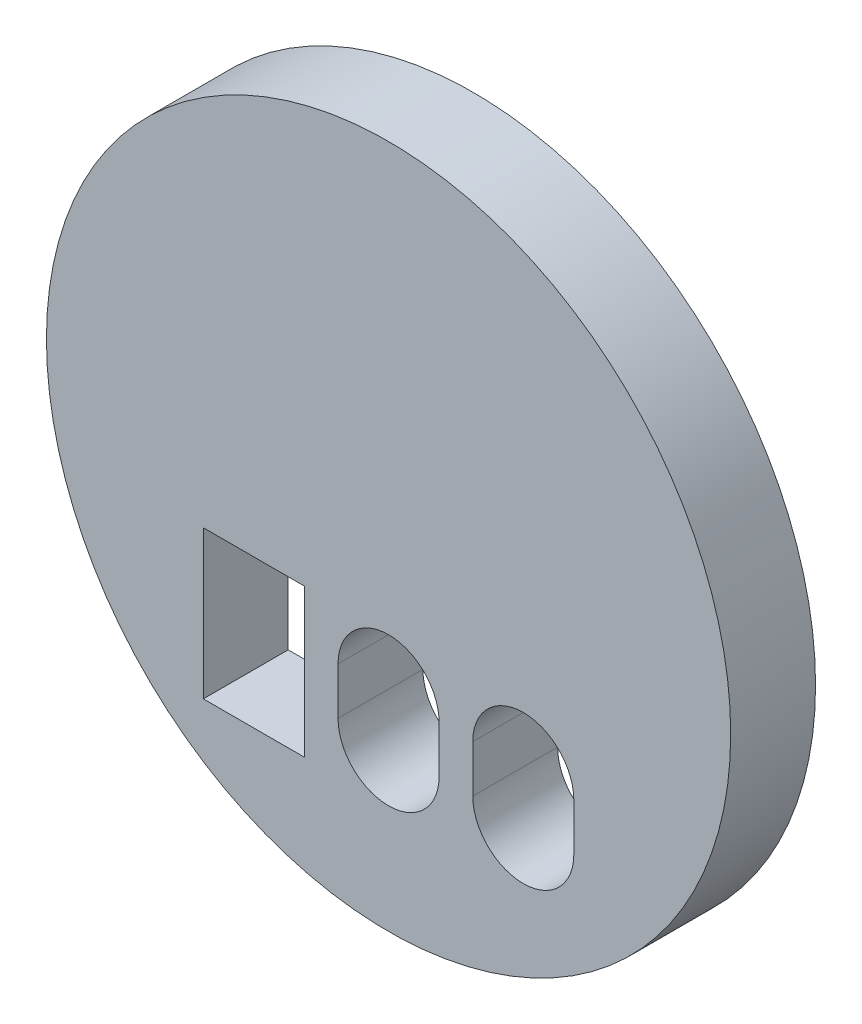
SolidWorks part; units mm, degrees
ref_plane "Plan de face" through (0, 0, 0) normal (0, 0, 1) x (1, 0, 0)
ref_plane "Plan de dessus" through (0, 0, 0) normal (0, 1, 0) x (1, 0, 0)
ref_plane "Plan de droite" through (0, 0, 0) normal (1, 0, 0) x (0, 0, -1)
sketch "Model" plane through (0, 0, 0) normal (0, 0, 1) x (1, 0, 0)
  line L0 (-3.4925, -4.397) -> (-3.4925, -1.603)
  line L1 (-3.4925, -1.603) -> (-1.5875, -1.603)
  line L2 (-1.5875, -1.603) -> (-1.5875, -4.397)
  line L3 (-1.5875, -4.397) -> (-3.4925, -4.397)
  line L4 (0.9525, -2.5555) -> (0.9525, -3.4445)
  line L5 (-0.9525, -3.4445) -> (-0.9525, -2.5555)
  line L6 (3.4925, -2.5555) -> (3.4925, -3.4445)
  line L7 (1.5875, -3.4445) -> (1.5875, -2.5555)
  line L8 (0.785, 3.92) -> (1.375, 3.92) construction
  line L9 (1.375, 3.92) -> (1.375, 3.28) construction
  line L10 (1.375, 3.28) -> (0.785, 3.28) construction
  line L11 (0.785, 3.28) -> (0.785, 3.92) construction
  line L12 (-0.175, 3.92) -> (0.415, 3.92) construction
  line L13 (0.415, 3.92) -> (0.415, 3.28) construction
  line L14 (0.415, 3.28) -> (-0.175, 3.28) construction
  line L15 (-0.175, 3.28) -> (-0.175, 3.92) construction
  line L16 (0.005, -0.612) -> (0.005, -0.305) construction
  line L17 (-0.005, -0.305) -> (-0.005, -0.612) construction
  circle A0 centre (-0.966, 2.103) radius 0.3615 construction
  circle A1 centre (1.015, -0.634) radius 0.281 construction
  circle A2 centre (-1.015, -0.634) radius 0.281 construction
  circle A3 centre (0.966, 2.103) radius 0.3615 construction
  circle A4 centre (0, 2.103) radius 0.306 construction
  arc A5 (-0.9525, -3.4445) -> (0.9525, -3.4445) centre (0, -3.4445) ccw
  arc A6 (0.9525, -2.5555) -> (-0.9525, -2.5555) centre (0, -2.5555) ccw
  arc A7 (1.5875, -3.4445) -> (3.4925, -3.4445) centre (2.54, -3.4445) ccw
  arc A8 (3.4925, -2.5555) -> (1.5875, -2.5555) centre (2.54, -2.5555) ccw
  arc A9 (0.612, 0) -> (-0.005, -0.612) centre (0, 0) ccw construction
  arc A10 (0.005, -0.612) -> (0.612, 0) centre (0, 0) ccw construction
  arc A11 (0.005, -0.305) -> (-0.305, 0) centre (0, 0) ccw construction
  arc A12 (-0.305, 0) -> (-0.005, -0.305) centre (0, 0) ccw construction
  circle A13 centre (0, 0) radius 6.45
extrude "Boss.-Extru.1" add sketch "Model" along normal blind 1.6
